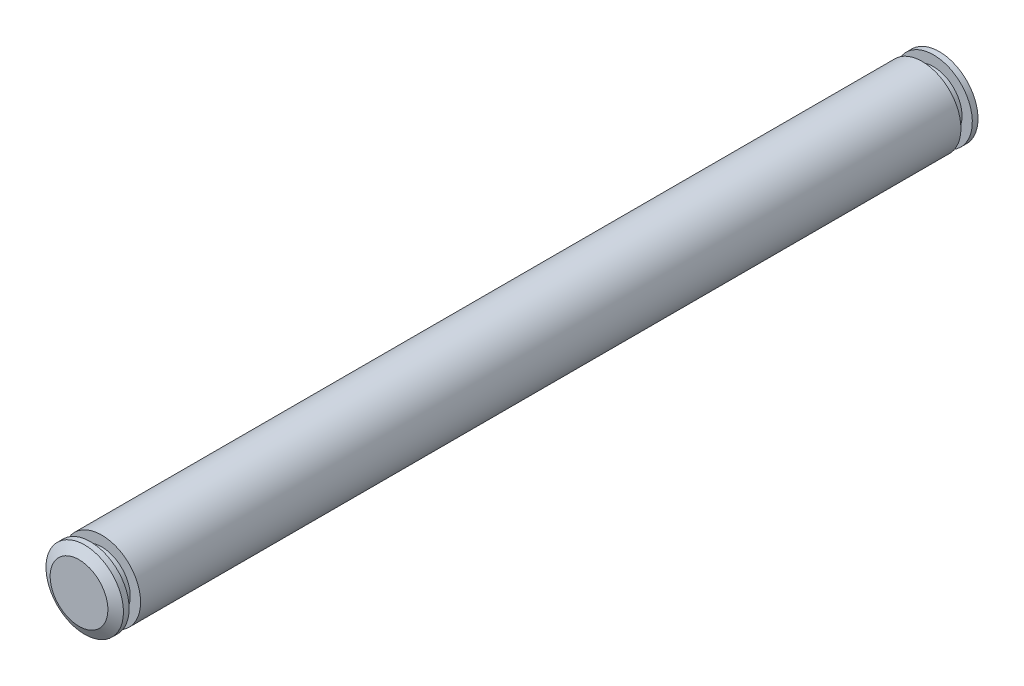
SolidWorks part; units mm, degrees
material "1.2210 (115CrV3)"
ref_plane "Front Plane" through (0, 0, 0) normal (0, 0, 1) x (1, 0, 0)
ref_plane "Top Plane" through (0, 0, 0) normal (0, 1, 0) x (1, 0, 0)
ref_plane "Right Plane" through (0, 0, 0) normal (1, 0, 0) x (0, 0, -1)
sketch "Sketch1" plane through (0, 0, 0) normal (1, 0, 0) x (0, 0, -1)
  line L0 (-38, 0) -> (-38, 3.4)
  line L1 (-38, 3.4) -> (2.4322, 3.4)
  line L5 (2.4322, 3.4) -> (38, 3.4)
  line L6 (38, 3.4) -> (38, 0)
  line L7 (38, 0) -> (-38, 0)
  line L8 (-38, 0) -> (-33.2337, 0) construction
  point P8 (0, 0)
  dimension "D1" = 6.8
  dimension "D2" = 76
revolve "Revolve1" add sketch "Sketch1" angle 360 about L8
chamfer "Chamfer1" distance 0.5 angle 60 2 edges at (0, -3.4, 38) (0, -3.4, -38)
sketch "Sketch2" plane through (0, 0, -38) normal (0, 0, -1) x (-1, 0, 0)
  circle A0 centre (0, 0) radius 2.5
  point P1 (4.7428, 0)
  dimension "D1" = 5
extrude "Cut-Extrude1" cut sketch "Sketch2" against normal blind 1 from offset 1 flip side to cut offset against normal yes
mirror "Mirror1" about plane through (0, 0, 0) normal (0, 0, 1) of "Cut-Extrude1"
